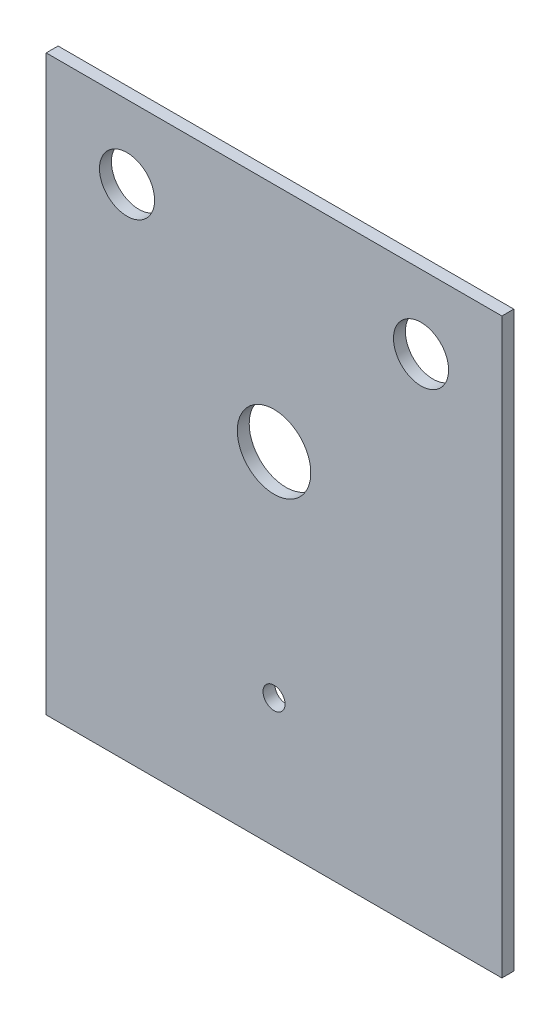
SolidWorks part; units mm, degrees
ref_plane "Front Plane" through (0, 0, 0) normal (0, 0, 1) x (1, 0, 0)
ref_plane "Top Plane" through (0, 0, 0) normal (0, 1, 0) x (1, 0, 0)
ref_plane "Right Plane" through (0, 0, 0) normal (1, 0, 0) x (0, 0, -1)
ref_plane "Plane1" through (0, 0, 0) normal (0, 0, -1) x (-1, 0, 0)
sketch "Sketch1" plane through (0, 0, 0) normal (0, 0, -1) x (-1, 0, 0)
  line L0 (-88.646, 83.82) -> (-104.394, 83.82)
  line L1 (-104.394, 83.82) -> (-104.394, 64.008)
  line L2 (-104.394, 64.008) -> (-88.646, 64.008)
  line L3 (-88.646, 64.008) -> (-88.646, 83.82)
  circle A0 centre (-96.52, 75.819) radius 1.27
  circle A1 centre (-91.44, 81.28) radius 0.952
  circle A2 centre (-96.52, 68.453) radius 0.381
  circle A3 centre (-101.6, 81.28) radius 0.952
extrude "Boss-Extrude1" add sketch "Sketch1" against normal blind 0.4115
